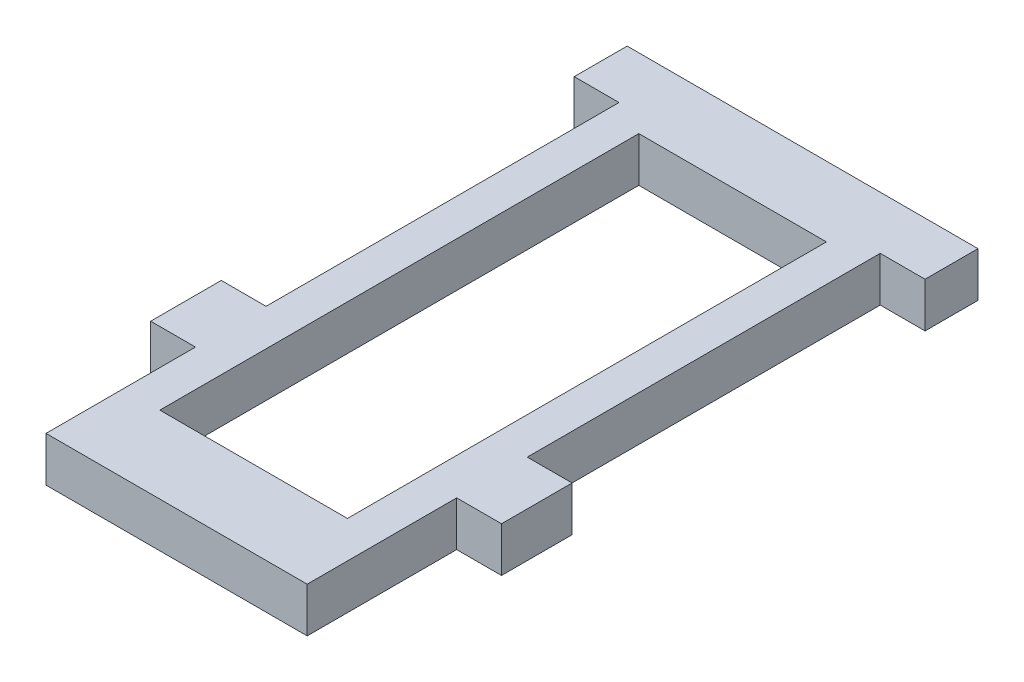
SolidWorks part; units mm, degrees
ref_plane "Front Plane" through (0, 0, 0) normal (0, 0, 1) x (1, 0, 0)
ref_plane "Top Plane" through (0, 0, 0) normal (0, 1, 0) x (1, 0, 0)
ref_plane "Right Plane" through (0, 0, 0) normal (1, 0, 0) x (0, 0, -1)
sketch "Sketch1" plane through (0, 0, 0) normal (0, 1, 0) x (1, 0, 0)
  line L0 (-37, -88.675) -> (-37, -46.325)
  line L1 (-37, -46.325) -> (-49.7, -46.325)
  line L2 (-49.7, -46.325) -> (-49.7, -26.325)
  line L3 (-49.7, -26.325) -> (-37, -26.325)
  line L4 (-37, -26.325) -> (-37, 73.675)
  line L5 (-37, 73.675) -> (-49.7, 73.675)
  line L6 (-49.7, 73.675) -> (-49.7, 88.675)
  line L7 (-49.7, 88.675) -> (49.7, 88.675)
  line L8 (49.7, 88.675) -> (49.7, 73.675)
  line L9 (49.7, 73.675) -> (37, 73.675)
  line L10 (37, 73.675) -> (37, -26.325)
  line L11 (37, -26.325) -> (49.7, -26.325)
  line L12 (49.7, -26.325) -> (49.7, -46.325)
  line L13 (49.7, -46.325) -> (37, -46.325)
  line L14 (37, -46.325) -> (37, -88.675)
  line L15 (37, -88.675) -> (-37, -88.675)
  line L16 (0, 88.675) -> (0, -88.675) construction
  line L18 (-26.575, 68.85) -> (26.575, 68.85)
  line L19 (-26.575, 68.85) -> (-26.575, -66.85)
  line L20 (-26.575, -66.85) -> (26.575, -66.85)
  line L21 (26.575, 68.85) -> (26.575, -66.85)
  point P15 (0, 88.675)
  point P20 (0, 68.85)
  point P21 (-26.575, 65.104)
  dimension "D1" = 12.7
  dimension "D2" = 20
  dimension "D3" = 100
  dimension "D4" = 15
  dimension "D5" = 42.35
  dimension "D6" = 74
  dimension "D7" = 135.7
  dimension "D8" = 53.15
  dimension "D9" = 21.825
extrude "Boss-Extrude1" add sketch "Sketch1" along normal mid plane 12.7
